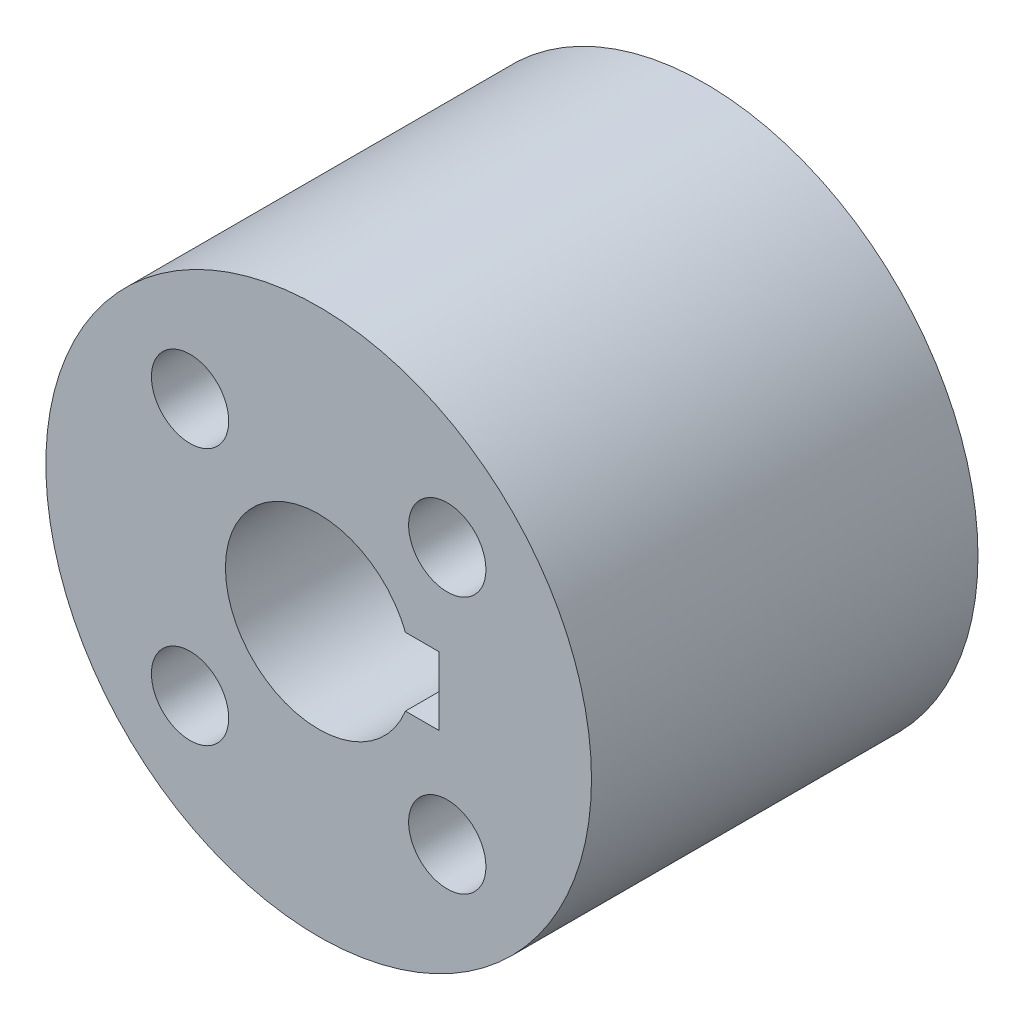
SolidWorks part; units mm, degrees
ref_plane "Ebene vorne" through (0, 0, 0) normal (0, 0, 1) x (1, 0, 0)
ref_plane "Ebene oben" through (0, 0, 0) normal (0, 1, 0) x (1, 0, 0)
ref_plane "Ebene rechts" through (0, 0, 0) normal (1, 0, 0) x (0, 0, -1)
sketch "Skizze1" plane through (0, 0, 0) normal (0, 0, 1) x (1, 0, 0)
  line L0 (4.1, 0) -> (4.1, 2.1941) construction
  line L1 (2.9, -1.5) -> (5.3, -1.5)
  line L2 (2.9, -1.5) -> (2.9, 1.5)
  line L3 (2.9, 1.5) -> (5.3, 1.5)
  line L4 (5.3, -1.5) -> (5.3, 1.5)
  line L5 (2.9, -1.5) -> (5.3, 1.5) construction
  line L6 (2.9, 1.5) -> (5.3, -1.5) construction
  line L7 (-4.1, 0) -> (-4.1, 2.1941) construction
  line L8 (0, 0) -> (5.6569, 5.6569) construction
  circle A0 centre (0, 0) radius 4.1
  circle A1 centre (0, 0) radius 12
  circle A2 centre (0, 0) radius 8
  circle A3 centre (5.6569, 5.6569) radius 1.7
  circle A4 centre (5.6569, -5.6569) radius 1.7
  circle A5 centre (-5.6569, -5.6569) radius 1.7
  circle A6 centre (-5.6569, 5.6569) radius 1.7
  point P3 (4.1, 0)
  point P25 (0, 0)
  dimension "D1" = 8.2
  dimension "D4" = 24
  dimension "D5" = 16
  dimension "D6" = 4
  dimension "D2" = 3
  dimension "D3" = 9.4
extrude "Aufsatz-Linear austragen1" add sketch "Skizze1" along normal blind 17 contours A1 A6 A2 A3 A4 A5 | A6 A2 A5 A4 A3 A0 L3 L4 L1
sketch "Skizze3" plane through (0, 0, 0) normal (0, 0, -1) x (-1, 0, 0)
  circle A1 centre (-5.6569, 5.6569) radius 3.5
  circle A2 centre (5.6569, 5.6569) radius 3.5
  circle A3 centre (5.6569, -5.6569) radius 3.5
  circle A4 centre (-5.6569, -5.6569) radius 3.5
  point P14 (0, 0)
  dimension "D1" = 4
extrude "Schnitt-Linear austragen1" cut sketch "Skizze3" against normal offset from surface (12 mm away) 5 up to face at (-3.9569, 5.6569, 17)
